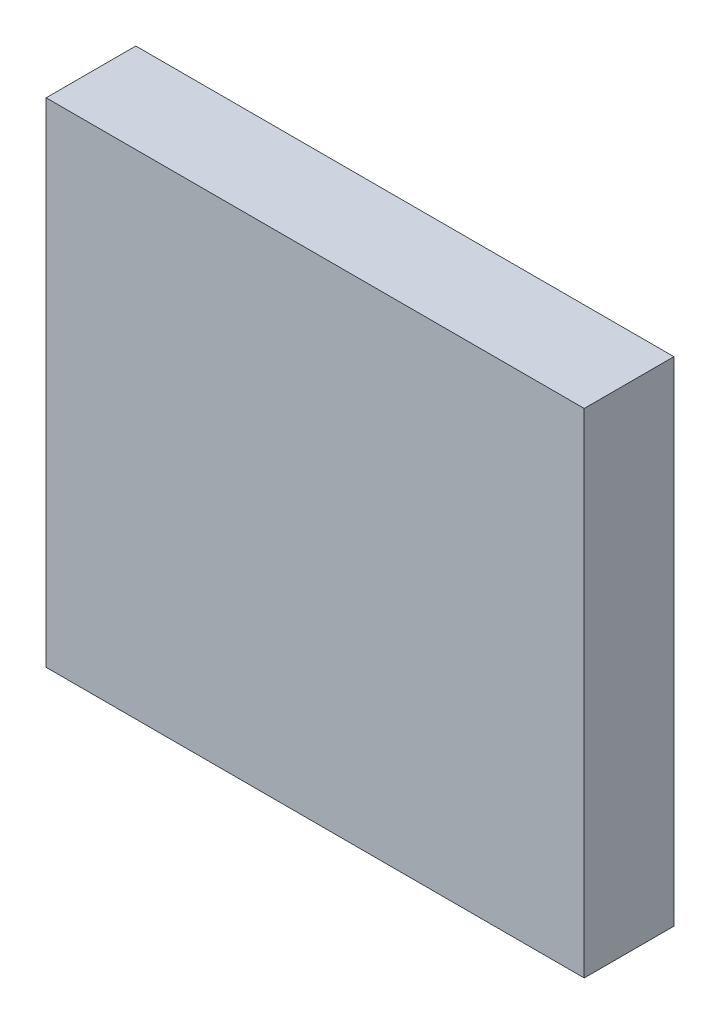
SolidWorks part; units mm, degrees
ref_plane "前视基准面" through (0, 0, 0) normal (0, 0, 1) x (1, 0, 0)
ref_plane "上视基准面" through (0, 0, 0) normal (0, 1, 0) x (1, 0, 0)
ref_plane "右视基准面" through (0, 0, 0) normal (1, 0, 0) x (0, 0, -1)
sketch "草图1" plane through (0, 0, 0) normal (0, 0, 1) x (1, 0, 0)
  line L1 (15, 13.75) -> (-15, 13.75)
  line L2 (15, 13.75) -> (15, -13.75)
  line L3 (15, -13.75) -> (-15, -13.75)
  line L4 (-15, 13.75) -> (-15, -13.75)
  line L5 (15, 13.75) -> (-15, -13.75) construction
  line L6 (15, -13.75) -> (-15, 13.75) construction
  point P0 (0, 0)
  dimension "D1" = 27.5
  dimension "D2" = 30
extrude "凸台-拉伸1" add sketch "草图1" along normal blind 5
